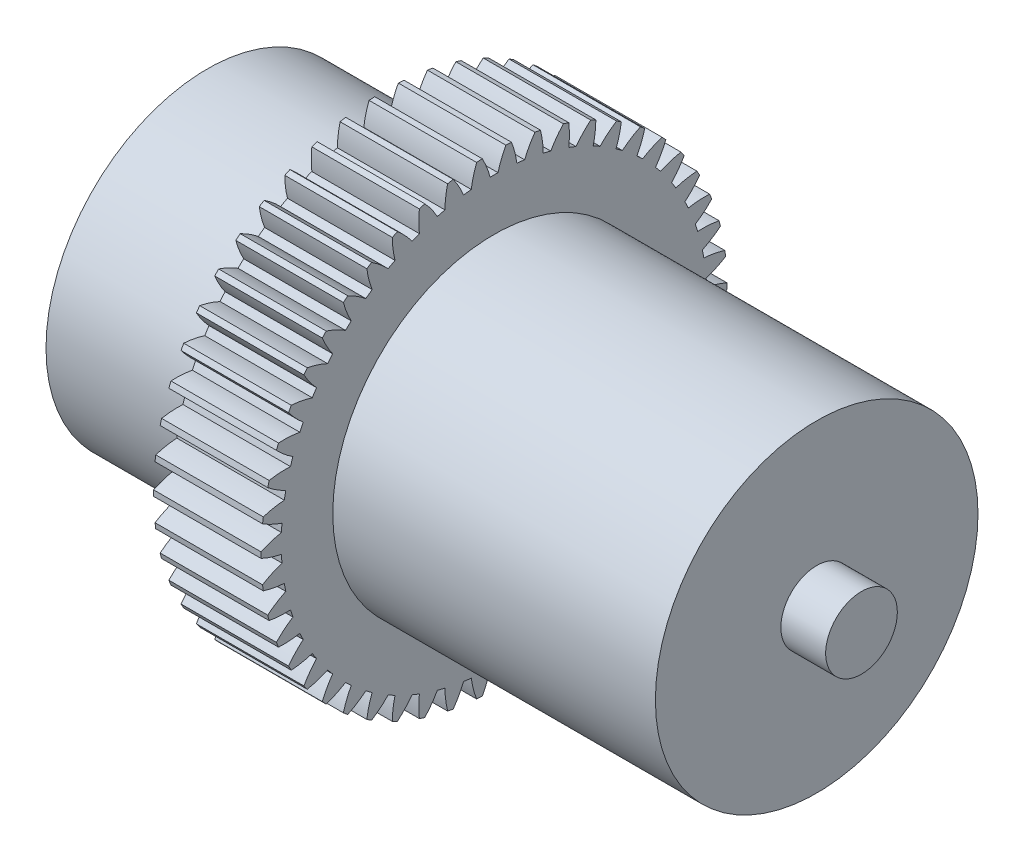
SolidWorks part; units mm, degrees
ref_plane "Plane1" through (0, 0, 0) normal (0, 0, 1) x (1, 0, 0)
ref_plane "Plane2" through (0, 0, 0) normal (0, 1, 0) x (1, 0, 0)
ref_plane "Plane3" through (0, 0, 0) normal (1, 0, 0) x (0, 0, -1)
sketch "HoldingSke" plane through (0, 0, 0) normal (0, 1, 0) x (1, 0, 0)
  line L0 (0, 0) -> (0.6428, -0.766)
  line L1 (-15, 0) -> (100, 0) construction
  line L2 (0, 0) -> (-2.1039, 2.3779)
  line L3 (0, 0) -> (-11.863, 4.5341)
  line L4 (0, 0) -> (5.5511, 6.6156)
  line L5 (0, 0) -> (-46.8476, -17.4728)
  line L6 (0, 0) -> (-9.9476, -6.7116)
  line L7 (-2.1039, 2.3779) -> (8.6586, 51.2059)
  line L8 (-76.2, 54.61) -> (-74.8, 54.61)
  line L9 (-71.009, 38.7566) -> (-53.1078, 45.2721)
  line L10 (-76.2, 71.12) -> (104.1128, 71.12)
  line L11 (0, 0) -> (-12, 0)
  line L12 (-76.2, 101.6) -> (-76.162, 101.6)
  line L13 (24.9733, 27.94) -> (52.9518, 28.4284)
  line L14 (24.9733, 27.94) -> (24.9743, 27.94)
  line L15 (24.9733, 27.94) -> (100.4006, 29.5858)
  line L16 (-63.627, -1) -> (-12.827, -1)
  circle A0 centre (0, 0) radius 4
  circle A1 centre (0, 0) radius 23.749
  circle A2 centre (0, 0) radius 37.5
  circle A3 centre (0, 0) radius 4
  dimension "MHD" = 47.498
  dimension "Hub_dia" = 75
  dimension "Bore" = 8
  dimension "MBD" = 8
  dimension "Num_teeth" = 50
  dimension "Pitch" = 1
  dimension "Overall_len" = 50
  dimension "Show_teeth" = 50
  dimension "Thickness" = 12
  dimension "OAL" = 50.0001
  dimension "T_dim" = 1.4
  dimension "Ap" = 20
  dimension "H" = 19.05
  dimension "Pitch_radius" = 180.3128
  dimension "Width" = 12
  dimension "Backlash" = 0.038
  dimension "Addendum_fac" = 1
  dimension "Dedendum_fac" = 1.25
  dimension "Clearance_fac" = 0.25
  dimension "Dedendum_add" = 0.001
  dimension "Module" = 1
sketch "BasProSke" plane through (0, 0, 0) normal (0, 1, 0) x (1, 0, 0)
  line L0 (-10, 0) -> (60, 0) construction
  line L1 (0, 0) -> (0, 26)
  line L2 (0, 0) -> (12, 0)
  line L3 (12, 0) -> (12, 26)
  line L4 (12, 26) -> (0, 26)
  dimension "Thickness" = 12
  dimension "Diameter" = 52
revolve "Base-Revolve" add sketch "BasProSke" angle 360 about L0
sketch "TooCutSke" plane through (0, 0, 0) normal (1, 0, 0) x (0, 0, -1)
  line L1 (0, 0) -> (0, 107) construction
  line L2 (0, 0) -> (-0.8518, 24.9855) construction
  line L3 (0, 0) -> (-3.1382, 49.8807) construction
  line L4 (-0.8518, 24.9855) -> (-1.5691, 24.9404) construction
  arc A0 (0.4377, 23.745) -> (-0.4377, 23.745) centre (0, 0) ccw
  arc A1 (1.3294, 25.9914) -> (-1.3294, 25.9914) centre (0, 0) ccw
  circle A2 centre (0, 0) radius 25 construction
  circle A3 centre (0, 0) radius 23.4923 construction
  arc A4 (-0.4377, 23.745) -> (-1.3294, 25.9914) centre (-10.1099, 21.2056) ccw
  arc A5 (1.3294, 25.9914) -> (0.4377, 23.745) centre (10.1099, 21.2056) ccw
  dimension "Root_dia" = 47.498
  dimension "Overcut_dia" = 52.0508
  dimension "Pitch_dia" = 50
  dimension "Base_dia" = 46.9846
  dimension "Flank_rad" = 10
  dimension "Half_ang" = 3.6
  dimension "Half_CT" = 0.7188
extrude "ToothCut" cut sketch "TooCutSke" along normal through all
fillet "Breaks" [suppressed] radius 0.02
fillet "RootFillets" [suppressed] radius 0.251
pattern_circular "TeethCuts" count 50 every 7.2 about axis through (-10, 0, 0) along (1, 0, 0) of "ToothCut", "RootFillets", "Breaks"
sketch "HubNeaOneSke" plane through (0, 0, 0) normal (-1, 0, 0) x (0, 0, 1)
  circle A0 centre (0, 0) radius 23.749
  dimension "Diameter" = 47.498
extrude "HubNearOne" [suppressed] add sketch "HubNeaOneSke" along normal blind 38.0001
sketch "HubNeaBotSke" plane through (0, 0, 0) normal (-1, 0, 0) x (0, 0, 1)
  circle A0 centre (0, 0) radius 23.749
  dimension "Diameter" = 47.498
extrude "HubNearBoth" [suppressed] add sketch "HubNeaBotSke" along normal blind 19
ref_plane "FarPln" through (12, 0, 0) normal (1, 0, 0) x (0, 0, -1)
sketch "HubFarSke" plane through (12, 0, 0) normal (1, 0, 0) x (0, 0, -1)
  circle A0 centre (0, 0) radius 23.749
  dimension "Diameter" = 47.498
extrude "HubFar" [suppressed] add sketch "HubFarSke" along normal blind 19
sketch "BorSke" plane through (0, 0, 0) normal (1, 0, 0) x (0, 0, -1)
  circle A0 centre (0, 0) radius 4
  dimension "Diameter" = 8
extrude "Bore" cut sketch "BorSke" along normal mid plane 100.0001
sketch "KeySke" plane through (0, 0, 0) normal (1, 0, 0) x (0, 0, -1)
  line L0 (-1, 0) -> (-1, 5.4)
  line L1 (-1, 5.4) -> (1, 5.4)
  line L2 (1, 5.4) -> (1, 0)
  line L3 (0, 0) -> (0, 34) construction
  line L4 (-1, 0) -> (1, 0)
  dimension "Offset" = 5.4
  dimension "Width" = 2
extrude "Keyway" [suppressed] cut sketch "KeySke" along normal mid plane 100.0001
pattern_circular "Keyway2" [suppressed] count 2 every 90 about axis through (-10, 0, 0) along (1, 0, 0)
sketch "Sketch1" plane through (12, 0, 0) normal (1, 0, 0) x (0, 0, -1)
  circle A0 centre (0, 0) radius 18
  dimension "D1" = 36
extrude "Boss-Extrude1" add sketch "Sketch1" along normal blind 36
sketch "Sketch2" plane through (48, 0, 0) normal (1, 0, 0) x (0, 0, -1)
  circle A0 centre (0, 0) radius 4
  dimension "D1" = 8
extrude "Boss-Extrude2" add sketch "Sketch2" along normal blind 5
sketch "Sketch3" plane through (0, 0, 0) normal (-1, 0, 0) x (0, 0, 1)
  circle A0 centre (0, 0) radius 18
  dimension "D1" = 36
extrude "Boss-Extrude3" add sketch "Sketch3" along normal blind 20
equation "' \"Module@HoldingSke\" = 6.35"
equation "' \"Num_teeth@HoldingSke\" = 12"
equation "' \"Ap@HoldingSke\" =  20"
equation "' \"Ap@HoldingSke\" = 20"
equation "' \"Width@HoldingSke\" = 0.5 * 25.4"
equation "' \"Hub_dia@HoldingSke\"= 1 * 25.4"
equation "' \"Hub_dia@HoldingSke\" = 1 * 25.4"
equation "' \"Overall_len@HoldingSke\" = 1.0 * 25.4"
equation "' \"Bore@HoldingSke\" = 0.75 * 25.4"
equation "' \"T_dim@HoldingSke\" = 0.1 * 25.4"
equation "' \"Width@KeySke\" = 0.25 * 25.4"
equation "' \"Show_teeth@HoldingSke\" = 13"
equation "' \"Backlash@HoldingSke\" = 0.009 * 25.4"
equation "' \"Addendum_fac@HoldingSke\" = 1.0"
equation "' \"Dedendum_fac@HoldingSke\" = 1.25"
equation "' \"Dedendum_add@HoldingSke\" = 0.00005 * 25.4"
equation "' \"Clearance_fac@HoldingSke\" = 0.25"
equation "\"Pitch@HoldingSke\" = 1 / \"Module@HoldingSke\""
equation "\"Overcut_dia@TooCutSke\" = (\"Num_teeth@HoldingSke\" + 2 * \"Addendum_fac@HoldingSke\") / \"Pitch@HoldingSke\" + 0.002 * 25.4"
equation "\"Pitch_dia@TooCutSke\" = \"Num_teeth@HoldingSke\" / \"Pitch@HoldingSke\""
equation "\"Base_dia@TooCutSke\" = \"Num_teeth@HoldingSke\" / \"Pitch@HoldingSke\" * cos((\"Ap@HoldingSke\"  * 3.14159265 / 180))"
equation "\"Root_dia@TooCutSke\" = (\"Num_teeth@HoldingSke\" + 2) / \"Pitch@HoldingSke\" - 2 * (\"Addendum_fac@HoldingSke\" + \"Dedendum_fac@HoldingSke\") / \"Pitch@HoldingSke\" - \"Dedendum_add@HoldingSke\" * 2"
equation "\"Half_ang@TooCutSke\" = 180 / \"Num_teeth@HoldingSke\""
equation "\"Half_CT@TooCutSke\" = \"Num_teeth@HoldingSke\" / \"Pitch@HoldingSke\" * sin((3.14159265 / 2 / \"Num_teeth@HoldingSke\")) / 2 - 7 * \"Backlash@HoldingSke\" / 4"
equation "\"Flank_rad@TooCutSke\" = \"Num_teeth@HoldingSke\" / \"Pitch@HoldingSke\" / 5"
equation "\"Radius@RootFillets\" = \"Clearance_fac@HoldingSke\" / \"Pitch@HoldingSke\" + \"Dedendum_add@HoldingSke\""
equation "\"Break_rad@Breaks\" = 0.02 / \"Pitch@HoldingSke\""
equation "\"Thickness@HoldingSke\" = \"Width@HoldingSke\""
equation "\"OAL@HoldingSke\" = \"Thickness@HoldingSke\""
equation "\"MHD@HoldingSke\" = (\"Num_teeth@HoldingSke\" + 2) / \"Pitch@HoldingSke\" - 2 * (\"Addendum_fac@HoldingSke\" + \"Dedendum_fac@HoldingSke\")  / \"Pitch@HoldingSke\" - \"Dedendum_add@HoldingSke\" * 2"
equation "\"MBD@HoldingSke\" = (\"Num_teeth@HoldingSke\" + 2) / \"Pitch@HoldingSke\" - 2 * (\"Addendum_fac@HoldingSke\" + \"Dedendum_fac@HoldingSke\")  / \"Pitch@HoldingSke\" - \"Dedendum_add@HoldingSke\" * 2 - 0.002 * 25.4"
equation "\"MHD@HoldingSke\" = ((sgn( \"MHD@HoldingSke\" - \"Hub_dia@HoldingSke\" )-1)*( \"MHD@HoldingSke\" - \"Hub_dia@HoldingSke\" ))/-2+ \"Hub_dia@HoldingSke\""
equation "\"MBD@HoldingSke\" = ((sgn( \"MBD@HoldingSke\" - \"Bore@HoldingSke\" )-1)*( \"MBD@HoldingSke\" - \"Bore@HoldingSke\" ))/-2+ \"Bore@HoldingSke\""
equation "\"OAL@HoldingSke\" = ((sgn( \"OAL@HoldingSke\" - \"Overall_len@HoldingSke\" )+1)*( \"OAL@HoldingSke\" - \"Overall_len@HoldingSke\" ))/2 + \"Overall_len@HoldingSke\" + 0.000002 * 25.4"
equation "\"Num_teeth@TeethCuts\" = int( \"Show_teeth@HoldingSke\" ) + 1"
equation "\"Num_teeth@TeethCuts\" = ((sgn( \"Num_teeth@TeethCuts\" - \"Num_teeth@HoldingSke\" )-1)*( \"Num_teeth@TeethCuts\" - \"Num_teeth@HoldingSke\" ))/-2+ \"Num_teeth@HoldingSke\""
equation "\"Num_teeth@TeethCuts\" = ((sgn( \"Num_teeth@TeethCuts\" - 2.0)+1)*( \"Num_teeth@TeethCuts\" - 2.0))/2 +2.0"
equation "\"Angle@TeethCuts\" = 360.0 / \"Num_teeth@HoldingSke\""
equation "\"Diameter@BasProSke\" = (\"Num_teeth@HoldingSke\" + 2 * \"Addendum_fac@HoldingSke\") / \"Pitch@HoldingSke\""
equation "\"Thickness@BasProSke\"  = \"Thickness@HoldingSke\""
equation "' \"Fillet_rad@BasProSke\" =  \"Thickness@HoldingSke\" * 0.05"
equation "' \"Fillet_rad@BasProSke\" = \"Thickness@HoldingSke\" * 0.05"
equation "\"MHD@HoldingSke\" = ((sgn( \"MHD@HoldingSke\" - \"Root_dia@TooCutSke\" )-1)*( \"MHD@HoldingSke\" - \"Root_dia@TooCutSke\" ))/-2+ \"Root_dia@TooCutSke\""
equation "\"Diameter@HubNeaOneSke\" = \"MHD@HoldingSke\""
equation "\"Length@HubNearOne\" = \"OAL@HoldingSke\" - \"Thickness@BasProSke\""
equation "\"Diameter@HubNeaBotSke\" = \"MHD@HoldingSke\""
equation "\"Length@HubNearBoth\" = ( \"OAL@HoldingSke\" - \"Thickness@BasProSke\" ) / 2.0"
equation "\"Thickness@FarPln\" = \"Thickness@BasProSke\""
equation "\"Diameter@HubFarSke\" = \"MHD@HoldingSke\""
equation "\"Length@HubFar\" = ( \"OAL@HoldingSke\" - \"Thickness@BasProSke\" ) / 2.0"
equation "\"Diameter@BorSke\" = \"MBD@HoldingSke\""
equation "\"D1@Bore\" = \"OAL@HoldingSke\" * 2.0"
equation "\"D1@Keyway\" = \"OAL@HoldingSke\" * 2.0"
equation "\"Offset@KeySke\" = \"T_dim@HoldingSke\" + \"MBD@HoldingSke\" / 2.0"
